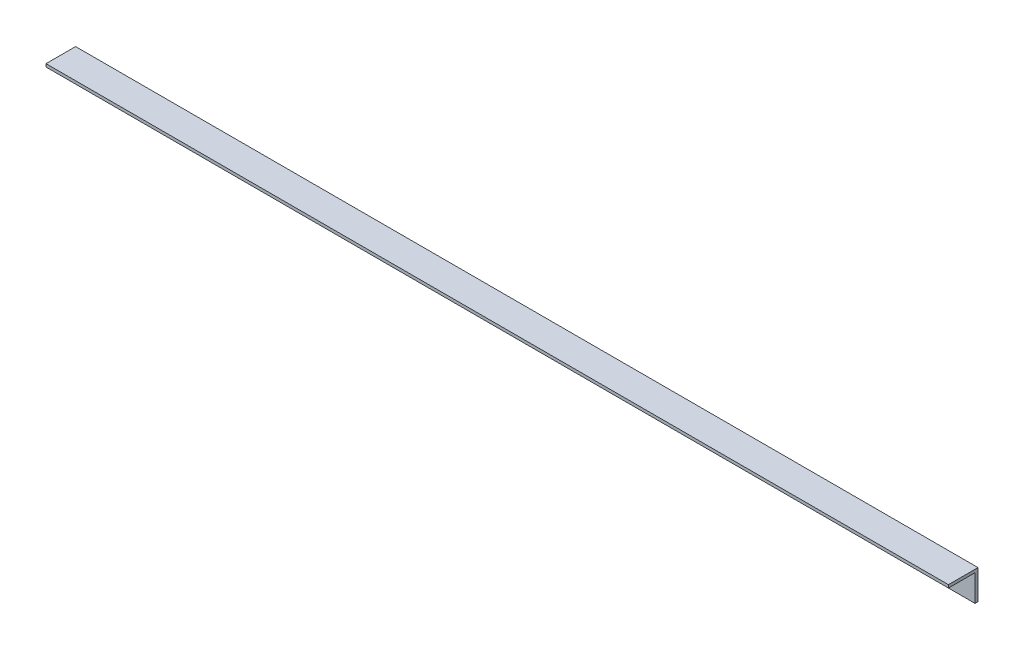
SolidWorks part; units mm, degrees
ref_plane "Plan de face" through (0, 0, 0) normal (0, 0, 1) x (1, 0, 0)
ref_plane "Plan de dessus" through (0, 0, 0) normal (0, 1, 0) x (1, 0, 0)
ref_plane "Plan de droite" through (0, 0, 0) normal (1, 0, 0) x (0, 0, -1)
sketch "Esquisse1" plane through (0, 0, 0) normal (0, 0, 1) x (1, 0, 0)
  line L1 (0, 0) -> (610, 0)
  line L2 (0, 0) -> (0, 20)
  line L3 (0, 20) -> (610, 20)
  line L4 (610, 0) -> (610, 20)
  dimension "D1" = 20
  dimension "D2" = 610
extrude "Boss.-Extru.1" add sketch "Esquisse1" along normal blind 2
sketch "Esquisse2" plane through (0, 0, 2) normal (0, 0, 1) x (1, 0, 0)
  line L0 (610, 0) -> (610, 20) construction
  line L1 (0, 20) -> (610, 20)
  line L2 (0, 20) -> (0, 18)
  line L3 (0, 18) -> (610, 18)
  line L4 (610, 20) -> (610, 18)
  dimension "D1" = 2
extrude "Boss.-Extru.2" add sketch "Esquisse2" along normal blind 18
